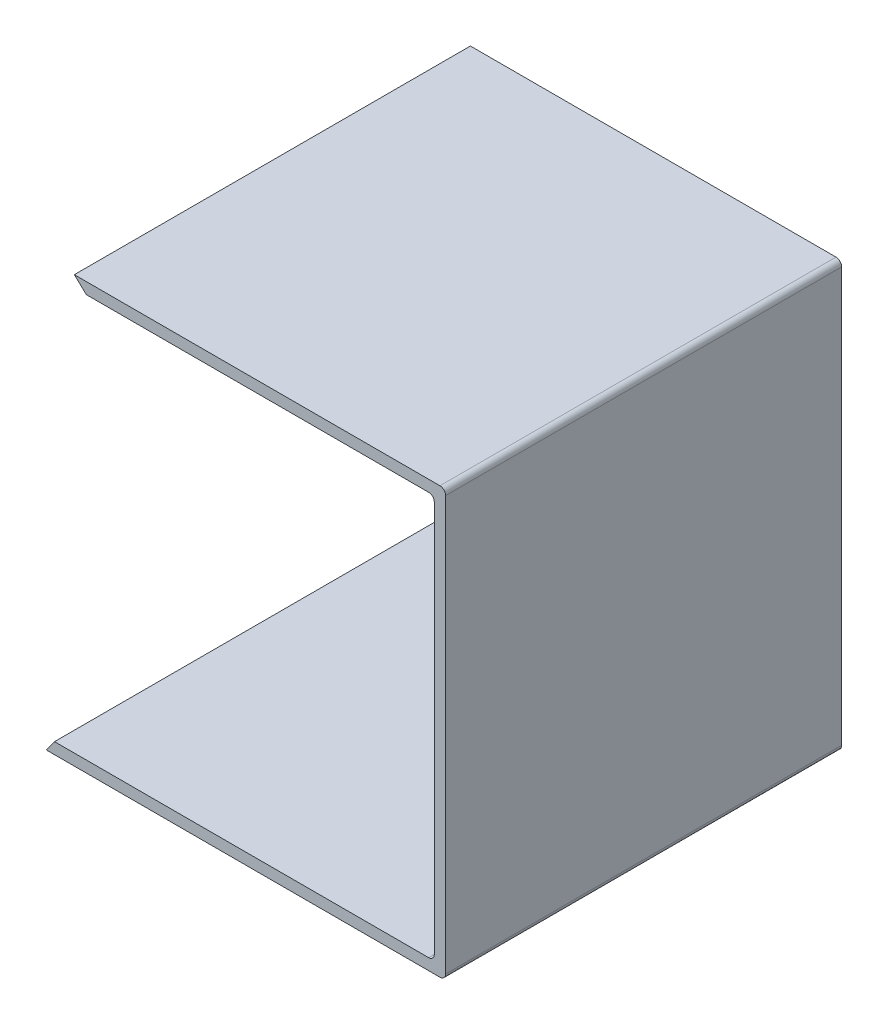
SolidWorks part; units mm, degrees
ref_plane "Plano frontal" through (0, 0, 0) normal (0, 0, 1) x (1, 0, 0)
ref_plane "Plano superior" through (0, 0, 0) normal (0, 1, 0) x (1, 0, 0)
ref_plane "Plano direito" through (0, 0, 0) normal (1, 0, 0) x (0, 0, -1)
sketch "Esboço1" plane through (0, 0, 0) normal (0, 0, 1) x (1, 0, 0)
  line L0 (0, 0) -> (2.8902, 4)
  line L1 (2.8902, 4) -> (135.13, 4)
  line L2 (137.13, 6) -> (137.13, 144.45)
  line L3 (135.13, 146.45) -> (14.13, 146.45)
  line L6 (141.13, 148.45) -> (141.13, 2)
  line L7 (139.13, 0) -> (0, 0)
  line L10 (14.13, 146.45) -> (9.8942, 150.45)
  line L11 (139.13, 150.45) -> (9.8942, 150.45)
  arc A0 (141.13, 2) -> (139.13, 0) centre (139.13, 2) cw
  arc A1 (135.13, 4) -> (137.13, 6) centre (135.13, 6) ccw
  arc A2 (139.13, 150.45) -> (141.13, 148.45) centre (139.13, 148.45) cw
  arc A3 (137.13, 144.45) -> (135.13, 146.45) centre (135.13, 144.45) ccw
  point P11 (141.13, 0)
  point P16 (141.13, 150.45)
  dimension "D8" = 2
  dimension "D1" = 4
  dimension "D2" = 4
  dimension "D3" = 127
  dimension "D4" = 54.15
  dimension "D5" = 141.13
  dimension "D6" = 4
  dimension "D7" = 131.2358
  dimension "D9" = 150.45
extrude "Ressalto-extrusão1" add sketch "Esboço1" along normal blind 140
